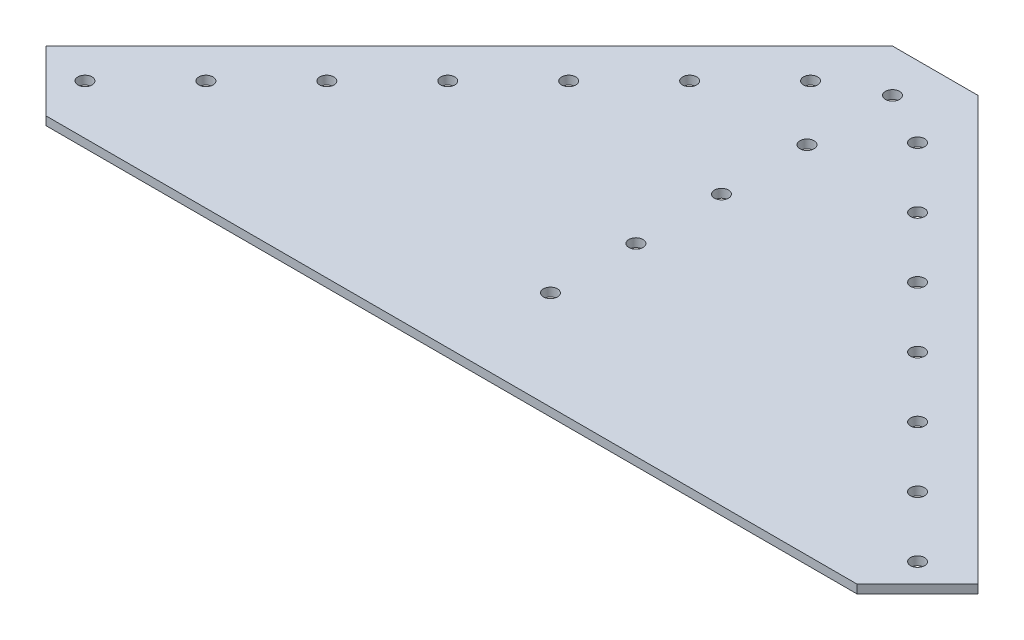
SolidWorks part; units mm, degrees
ref_plane "Front" through (0, 0, 0) normal (0, 0, 1) x (1, 0, 0)
ref_plane "Top" through (0, 0, 0) normal (0, 1, 0) x (1, 0, 0)
ref_plane "Right" through (0, 0, 0) normal (1, 0, 0) x (0, 0, -1)
sketch "Sketch1" plane through (0, 0, 0) normal (0, 1, 0) x (1, 0, 0)
  line L0 (0, 0) -> (25.4, 0)
  line L1 (25.4, 0) -> (151.1236, -125.7236)
  line L2 (0, 0) -> (-125.7236, -125.7236)
  line L3 (-125.7236, -125.7236) -> (-107.7631, -143.6841)
  line L4 (151.1236, -125.7236) -> (133.1631, -143.6841)
  line L5 (-107.7631, -143.6841) -> (133.1631, -143.6841)
  line L6 (12.7, 0) -> (12.7, -143.6841) construction
  dimension "D1" = 177.8
  dimension "D4" = 25.4
extrude "Boss-Extrude1" add sketch "Sketch1" along normal blind 2.54
sketch "Sketch2" plane through (0, 2.54, 0) normal (0, 1, 0) x (1, 0, 0)
  line L0 (12.7, -12.7) -> (12.7, 0) construction
  line L1 (25.4, 0) -> (0, 0) construction
  circle A0 centre (12.7, -12.7) radius 2.0955
  circle A1 centre (12.7, -38.1) radius 2.0955
  circle A2 centre (12.7, -63.5) radius 2.0955
  circle A3 centre (12.7, -88.9) radius 2.0955
  circle A4 centre (12.7, -114.3) radius 2.0955
  dimension "D2" = 4.191
  dimension "D1" = 12.7
  dimension "D3" = 5
extrude "Cut-Extrude1" cut sketch "Sketch2" against normal through all both and the other way through all
hole_wizard "#8 (0.199) Diameter Hole1" positions "Sketch3" profile "Sketch4" hole size "#8" standard "ANSI Inch" end condition through all
sketch "Sketch3" plane through (0, 0, 0) normal (0, -1, 0) x (-1, 0, 0)
  point P0 (21.1515, -39.1121)
  point P3 (39.1121, -57.0726)
  point P6 (57.0726, -75.0331)
  point P9 (75.0331, -92.9936)
  point P12 (92.9936, -110.9541)
  point P15 (110.9541, -128.9146)
  point P18 (-28.591, -21.1515)
  point P21 (-46.5515, -39.1121)
  point P24 (-64.5121, -57.0726)
  point P27 (-82.4726, -75.0331)
  point P30 (-100.4331, -92.9936)
  point P33 (-118.3936, -110.9541)
  point P36 (-136.3541, -128.9146)
  point P40 (3.191, -21.1515)
sketch "Sketch4" plane through (-21.1515, 0, 39.1121) normal (1, 0, 0) x (0, 0, -1)
  line L0 (0, 0) -> (0, 2.54)
  line L1 (0, 2.54) -> (2.0955, 2.54)
  line L2 (2.0955, 2.54) -> (2.0955, 0)
  line L5 (2.0955, 0) -> (0, 0)
  line L11 (0, -6.35) -> (0, 107.95) construction
  dimension "Thru Hole Dia." = 4.191
  dimension "Thru Hole Depth" = 2.54
